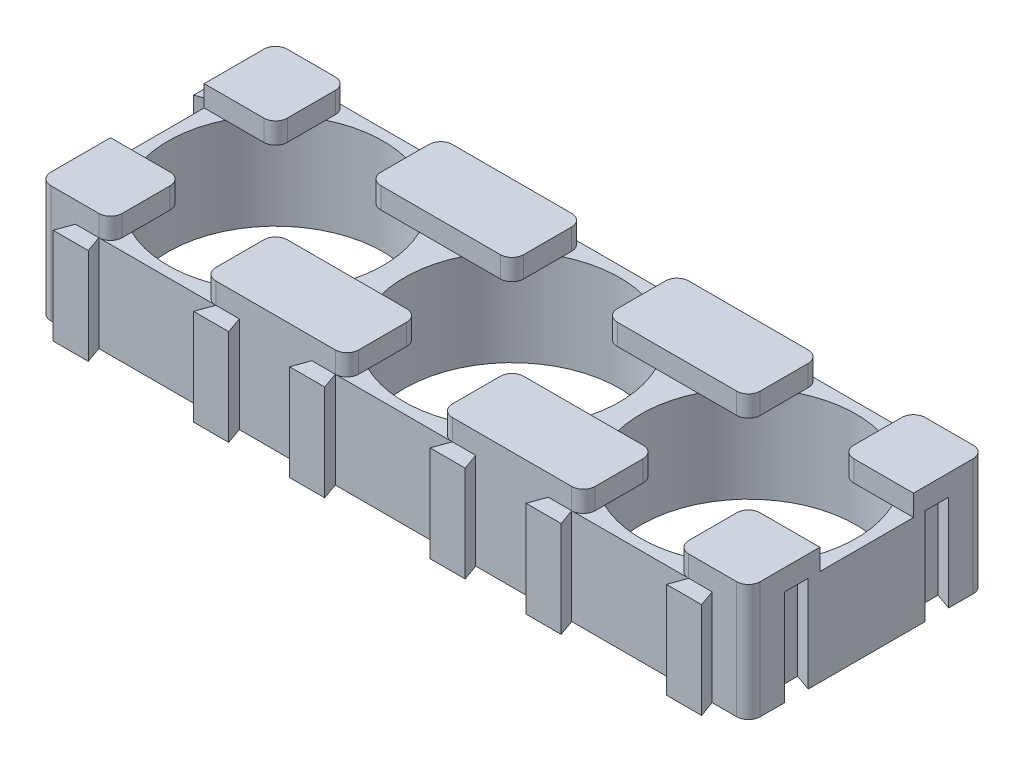
SolidWorks part; units mm, degrees
material "ABS"
ref_plane "Front Plane" through (0, 0, 0) normal (0, 0, 1) x (1, 0, 0)
ref_plane "Top Plane" through (0, 0, 0) normal (0, 1, 0) x (1, 0, 0)
ref_plane "Right Plane" through (0, 0, 0) normal (1, 0, 0) x (0, 0, -1)
sketch "Sketch1" plane through (0, 0, 0) normal (0, 1, 0) x (1, 0, 0)
  line L0 (-14.0032, 0) -> (15.5031, 0) construction
  line L1 (-9.1, 10.1) -> (-7, 10.1)
  line L2 (-10.1, 9.1) -> (-10.1, 7)
  line L3 (-9.1, -10.1) -> (-7, -10.1)
  line L4 (10.1, 9.1) -> (10.1, 7)
  line L5 (0, 12.8597) -> (0, -11.7289) construction
  line L6 (-10.1, 7) -> (-11.5, 7.5)
  line L7 (-11.5, 7.5) -> (-11.5, 4.5)
  line L8 (-11.5, 4.5) -> (-10.1, 5)
  line L9 (9.1, 10.1) -> (10.1, 10.1)
  line L10 (10.1, 10.1) -> (10.1, 9.1)
  line L11 (10.1, -9.1) -> (10.1, -10.1)
  line L12 (-10.1, 5) -> (-10.1, -5)
  line L13 (10.1, 5) -> (10.1, -5)
  line L14 (7, 10.1) -> (7.5, 8.7)
  line L15 (7.5, 8.7) -> (4.5, 8.7)
  line L16 (4.5, 8.7) -> (5, 10.1)
  line L17 (7, 10.1) -> (9.1, 10.1)
  line L18 (-7, -10.1) -> (-7.5, -11.5)
  line L19 (-7.5, -11.5) -> (-4.5, -11.5)
  line L20 (-4.5, -11.5) -> (-5, -10.1)
  line L21 (-5, -10.1) -> (5, -10.1)
  line L22 (-11.5, -4.5) -> (-10.1, -5)
  line L23 (-11.5, -7.5) -> (-11.5, -4.5)
  line L24 (-10.1, -7) -> (-11.5, -7.5)
  line L25 (-10.1, -7) -> (-10.1, -9.1)
  line L26 (4.5, -11.5) -> (5, -10.1)
  line L27 (7.5, -11.5) -> (4.5, -11.5)
  line L28 (7, -10.1) -> (7.5, -11.5)
  line L29 (7, -10.1) -> (9.1, -10.1)
  line L30 (-4.5, 8.7) -> (-5, 10.1)
  line L31 (-7.5, 8.7) -> (-4.5, 8.7)
  line L32 (-7, 10.1) -> (-7.5, 8.7)
  line L33 (-5, 10.1) -> (5, 10.1)
  line L34 (10.1, -7) -> (10.1, -5)
  line L35 (10.1, 5) -> (10.1, 7)
  line L36 (10.1, -10.1) -> (9.1, -10.1)
  line L37 (10.1, -7) -> (10.1, -9.1)
  line L38 (-9.1, 10.1) -> (-10.1, 10.1)
  line L39 (-10.1, 10.1) -> (-10.1, 9.1)
  line L40 (-10.1, -9.1) -> (-10.1, -10.1)
  line L41 (-10.1, -10.1) -> (-9.1, -10.1)
  circle A4 centre (0, 0) radius 9.2
  point P7 (-10.1, -10.1)
  point P10 (10.1, -10.1)
  point P13 (10.1, 10.1)
  dimension "D6" = 18.4
  dimension "D1" = 20.2
  dimension "D2" = 20.2
  dimension "D3" = 10.1
  dimension "D4" = 10.1
  dimension "D7" = 1.4
  dimension "D10" = 3
  dimension "D11" = 2
  dimension "D14" = 2
  dimension "D15" = 3
  dimension "D16" = 0.5
  dimension "D17" = 4.5
  dimension "D18" = 1.4
  dimension "D19" = 3
  dimension "D20" = 2
  dimension "D21" = 0.5
  dimension "D22" = 1.4
  dimension "D23" = 4.5
extrude "Boss-Extrude1" add sketch "Sketch1" along normal blind 8.2
sketch "Sketch2" plane through (0, 8.2, 0) normal (0, 1, 0) x (1, 0, 0)
  line L0 (-9.1, 4) -> (-5, 4)
  line L1 (-10.1, 5) -> (-10.1, -5) construction
  line L2 (-4, 5) -> (-4, 9.1)
  line L3 (5, 10.1) -> (-5, 10.1) construction
  line L4 (-5, 10.1) -> (-9.1, 10.1)
  line L5 (-10.1, 9.1) -> (-10.1, 5)
  line L6 (0, 2.2334) -> (0, -2.7823) construction
  line L7 (-2.0812, 0) -> (2.2435, 0) construction
  line L8 (9.1, 10.1) -> (10.1, 10.1)
  line L9 (5, 10.1) -> (9.1, 10.1)
  line L10 (4, 5) -> (4, 9.1)
  line L11 (9.1, 4) -> (5, 4)
  line L12 (9.1, -4) -> (5, -4)
  line L13 (10.1, 10.1) -> (10.1, 4)
  line L14 (5, -10.1) -> (9.1, -10.1)
  line L15 (4, -5) -> (4, -9.1)
  line L16 (-4, -5) -> (-4, -9.1)
  line L17 (-5, -10.1) -> (-9.1, -10.1)
  line L18 (-10.1, -9.1) -> (-10.1, -5)
  line L19 (-9.1, -4) -> (-5, -4)
  line L20 (10.1, -10.1) -> (10.1, 10.1) construction
  line L21 (10.1, 4) -> (9.1, 4)
  line L22 (9.1, -4) -> (10.1, -4)
  line L23 (10.1, -4) -> (10.1, -10.1)
  line L24 (10.1, -10.1) -> (9.1, -10.1)
  line L25 (-10.1, -9.1) -> (-10.1, -10.1)
  line L26 (-10.1, -7) -> (-10.1, -10.1) construction
  line L27 (-10.1, -10.1) -> (-9.1, -10.1)
  line L28 (-9.1, 10.1) -> (-10.1, 10.1)
  line L29 (-10.1, 10.1) -> (-10.1, 9.1)
  line L30 (-10.1, 5) -> (-10.1, 4)
  line L31 (-10.1, 4) -> (-9.1, 4)
  line L33 (-9.1, -4) -> (-10.1, -4)
  line L34 (-10.1, -4) -> (-10.1, -5)
  arc A0 (-4, 9.1) -> (-5, 10.1) centre (-5, 9.1) ccw
  arc A1 (-5, 4) -> (-4, 5) centre (-5, 5) ccw
  arc A5 (4, 9.1) -> (5, 10.1) centre (5, 9.1) cw
  arc A6 (5, 4) -> (4, 5) centre (5, 5) cw
  arc A8 (5, -4) -> (4, -5) centre (5, -5) ccw
  arc A11 (4, -9.1) -> (5, -10.1) centre (5, -9.1) ccw
  arc A12 (-5, -4) -> (-4, -5) centre (-5, -5) cw
  arc A13 (-4, -9.1) -> (-5, -10.1) centre (-5, -9.1) cw
  point P10 (-4, 10.1)
  point P13 (-4, 4)
  point P16 (-10.1, 4)
  dimension "D3" = 1
  dimension "D1" = 6.1
  dimension "D2" = 6.1
extrude "Boss-Extrude2" add sketch "Sketch2" along normal blind 1.8
sketch "Sketch4" plane through (0, 0, 0) normal (0, 1, 0) x (1, 0, 0)
  line L0 (0, 10.1) -> (41.5763, 10.1) construction
  line L1 (5, 10.1) -> (-5, 10.1) construction
pattern_linear "LPattern1" count 3 spacing 20.2 along (1, 0, 0) of "Boss-Extrude2", "Boss-Extrude1"
fillet "Fillet1" radius 1 4 edges at (50.5, 5, -10.1) (50.5, 5, 10.1) (-10.1, 5, 10.1) (-10.1, 5, -10.1)
sketch "Sketch5" plane through (0, 0, 0) normal (0, -1, 0) x (1, 0, 0)
  line L1 (50.5, 9.1) -> (50.5, -9.1) construction
  line L5 (50.5, -5) -> (49.1, -4.5)
  line L6 (49.1, -4.5) -> (49.1, -7.5)
  line L7 (49.1, -7.5) -> (50.5, -7)
  line L8 (50.5, -7) -> (50.5, -5)
  dimension "D1" = 1.4
extrude "Cut-Extrude1" cut sketch "Sketch5" against normal blind 8.2
mirror "Mirror1" about plane through (0, 0, 0) normal (0, 0, 1) of "Cut-Extrude1"
